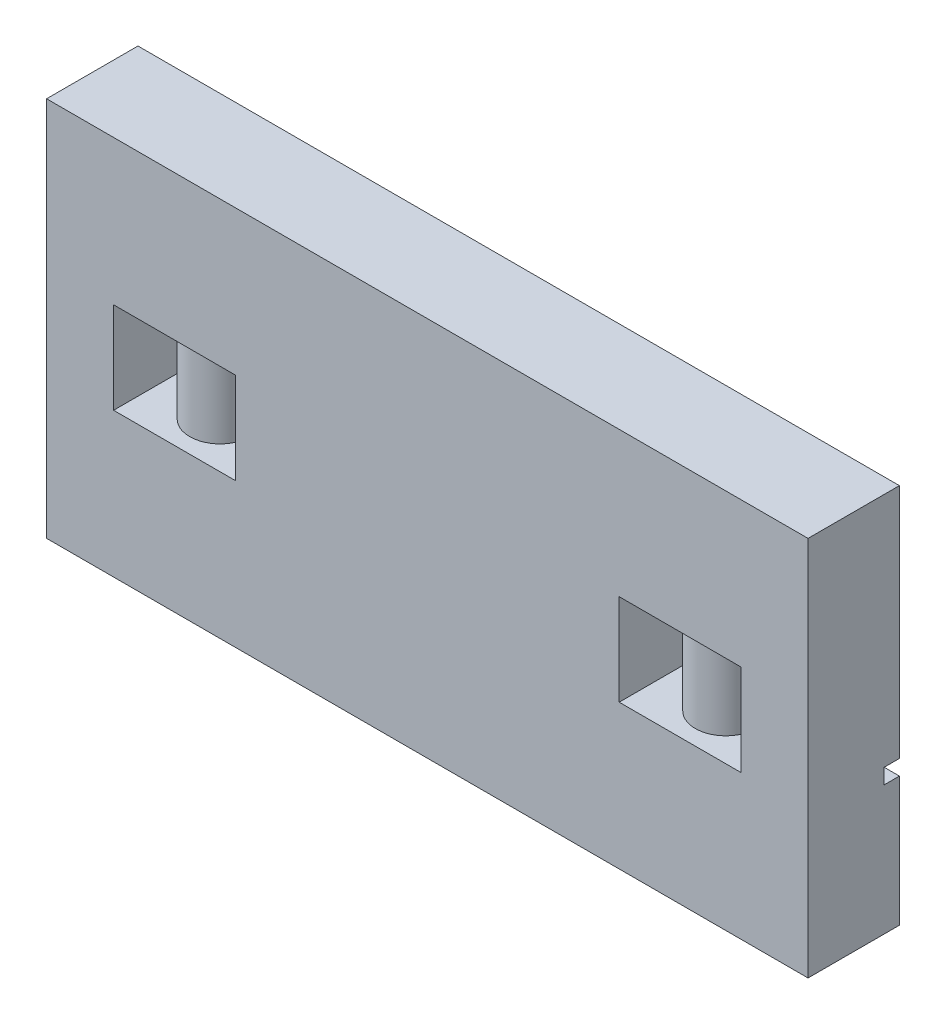
SolidWorks part; units mm, degrees
ref_plane "前视基准面" through (0, 0, 0) normal (0, 0, 1) x (1, 0, 0)
ref_plane "上视基准面" through (0, 0, 0) normal (0, 1, 0) x (1, 0, 0)
ref_plane "右视基准面" through (0, 0, 0) normal (1, 0, 0) x (0, 0, -1)
other "Configuration Table"
sketch "草图1" plane through (0, 0, 0) normal (0, 0, 1) x (1, 0, 0)
  line L0 (0, 0) -> (500, 0)
  line L1 (500, 0) -> (500, 250)
  line L2 (500, 250) -> (0, 250)
  line L3 (0, 250) -> (0, 0)
extrude "凸台-拉伸1" add sketch "草图1" along normal blind 60
sketch "草图3" plane through (0, 0, 0) normal (0, 0, 1) x (1, 0, 0)
  line L0 (0, 125) -> (500, 125) construction
  line L1 (0, 250) -> (0, 0) construction
  line L2 (500, 0) -> (500, 250) construction
  line L4 (250, 0) -> (250, 250) construction
  line L5 (500, 250) -> (0, 250) construction
  line L7 (0, 95) -> (500, 95) construction
  line L9 (0, 155) -> (500, 155) construction
sketch "草图5" plane through (0, 0, 0) normal (1, 0, 0) x (0, 0, -1)
  line L0 (0, 94.8425) -> (-10, 94.8425)
  line L1 (0, 0) -> (0, 250) construction
  line L2 (-10, 94.8425) -> (-10, 84.8425)
  line L3 (-10, 84.8425) -> (0, 84.8425)
  line L4 (0, 84.8425) -> (0, 94.8425)
extrude "切除-拉伸3" cut sketch "草图5" along normal blind 500
sketch "草图2" plane through (0, 0, 0) normal (0, -1, 0) x (1, 0, 0)
  line L0 (0, 30) -> (84, 30) construction
  line L1 (0, 60) -> (0, 0) construction
  line L2 (500, 60) -> (500, 0) construction
  line L3 (250, 0) -> (250, 60) construction
  line L4 (0, 0) -> (500, 0) construction
  line L5 (0, 60) -> (500, 60) construction
  line L6 (420, 30) -> (500, 30) construction
  line L8 (100, 60) -> (124, 60)
  line L9 (124, 60) -> (124, 0)
  line L10 (124, 0) -> (44, 0)
  line L11 (44, 0) -> (44, 60)
  line L12 (44, 60) -> (100, 60)
  line L13 (456, 60) -> (400, 60)
  line L15 (400, 60) -> (376, 60)
  line L16 (376, 60) -> (376, 0)
  line L17 (376, 0) -> (456, 0)
  line L18 (456, 0) -> (456, 60)
  circle A0 centre (84, 30) radius 20
  circle A2 centre (416, 30) radius 20
  dimension "D1" = 40
  dimension "D2" = 80
  dimension "D3" = 332
  dimension "D4" = 40
extrude "切除-拉伸4" cut sketch "草图2" against normal blind 60 from surface at -94.8425 starting at face at (250, 94.8425, 5)
